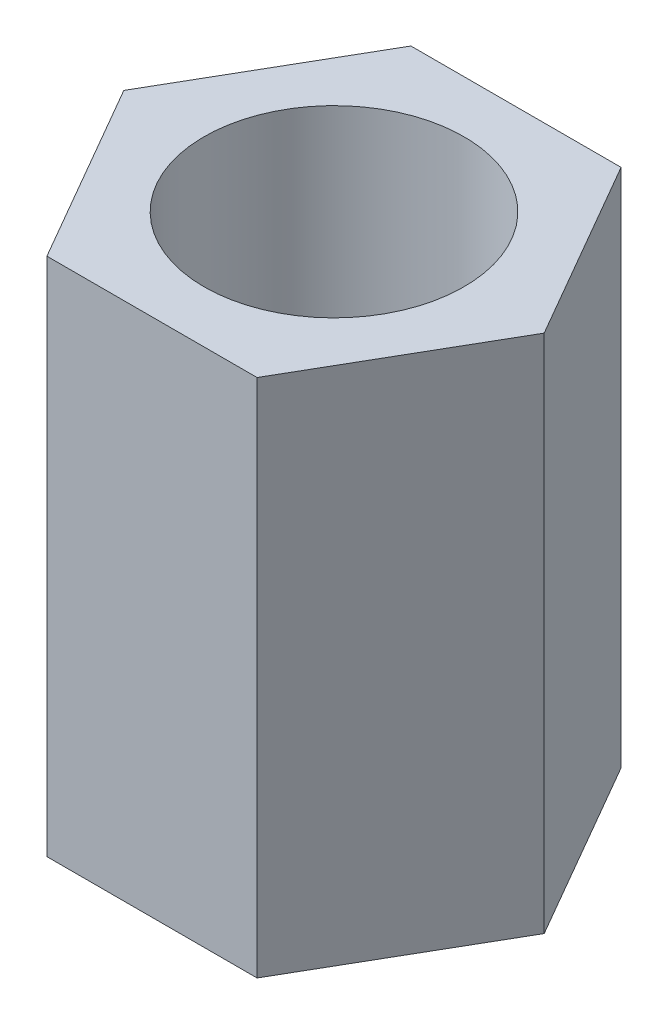
SolidWorks part; units mm, degrees
ref_plane "前视基准面" through (0, 0, 0) normal (0, 0, 1) x (1, 0, 0)
ref_plane "上视基准面" through (0, 0, 0) normal (0, 1, 0) x (1, 0, 0)
ref_plane "右视基准面" through (0, 0, 0) normal (1, 0, 0) x (0, 0, -1)
other "Configuration Table"
sketch "草图1" plane through (0, 0, 0) normal (0, 1, 0) x (1, 0, 0)
  line L1 (2.0207, 3.5) -> (-2.0207, 3.5)
  line L2 (-2.0207, 3.5) -> (-4.0415, 0)
  line L3 (-4.0415, 0) -> (-2.0207, -3.5)
  line L4 (-2.0207, -3.5) -> (2.0207, -3.5)
  line L5 (2.0207, -3.5) -> (4.0415, 0)
  line L6 (4.0415, 0) -> (2.0207, 3.5)
  circle A0 centre (0, 0) radius 3.5 construction
  circle A1 centre (0, 0) radius 2.5
  dimension "D2" = 5
  dimension "D1" = 7
extrude "凸台-拉伸1" add sketch "草图1" along normal blind 10
